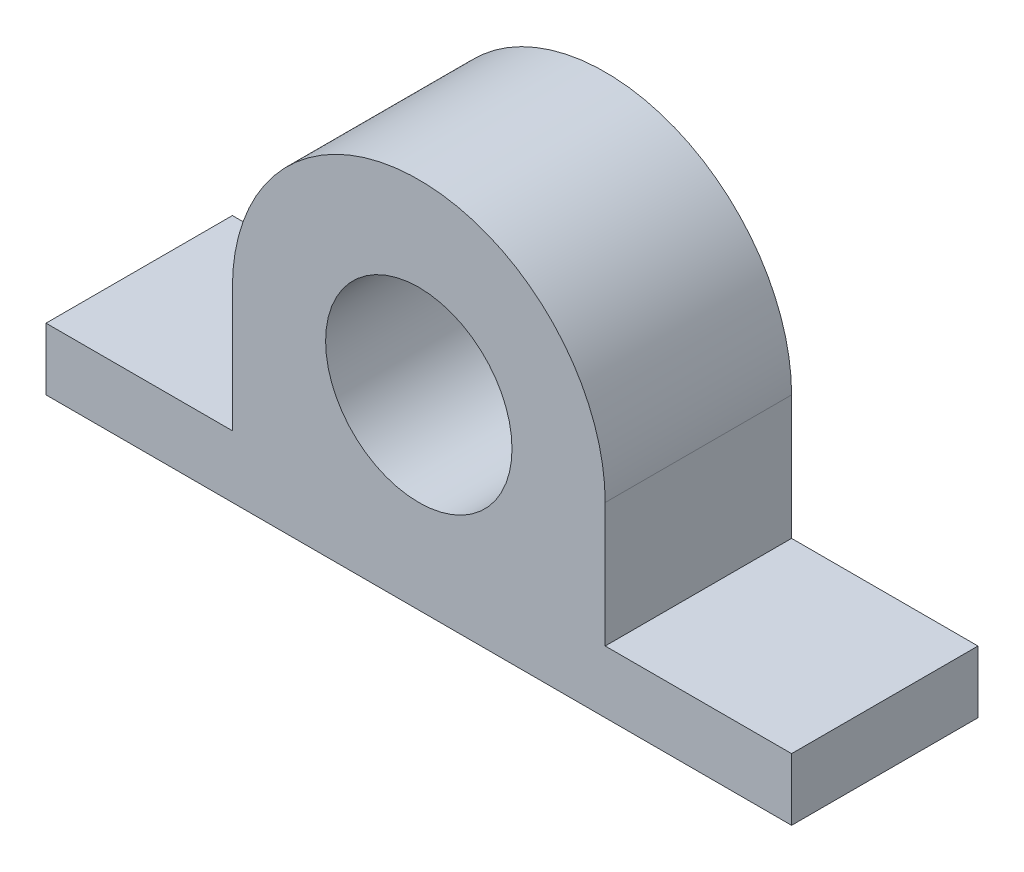
SolidWorks part; units mm, degrees
ref_plane "Front Plane" through (0, 0, 0) normal (0, 0, 1) x (1, 0, 0)
ref_plane "Top Plane" through (0, 0, 0) normal (0, 1, 0) x (1, 0, 0)
ref_plane "Right Plane" through (0, 0, 0) normal (1, 0, 0) x (0, 0, -1)
sketch "Sketch1" plane through (0, 0, 0) normal (0, 0, 1) x (1, 0, 0)
  line L0 (30, 25) -> (30, 5)
  line L1 (60, -5) -> (-60, -5)
  line L2 (60, -5) -> (60, 5)
  line L3 (60, 5) -> (30, 5)
  line L4 (-60, -5) -> (-60, 5)
  line L5 (60, -5) -> (60, 25) construction
  line L6 (-49.0564, 25) -> (70.5614, 25) construction
  line L7 (-30, 25) -> (-30, 5)
  line L9 (-22.3607, 5) -> (-23.3405, 5)
  line L10 (-60, 5) -> (-30, 5)
  circle A0 centre (0, 25) radius 15
  arc A1 (30, 25) -> (-30, 25) centre (0, 25) ccw
  point P0 (0, 0)
  dimension "D5" = 30
  dimension "D6" = 60
  dimension "D7" = 60
  dimension "D1" = 10
  dimension "D2" = 120
  dimension "D4" = 30
extrude "Boss-Extrude1" add sketch "Sketch1" along normal blind 30
